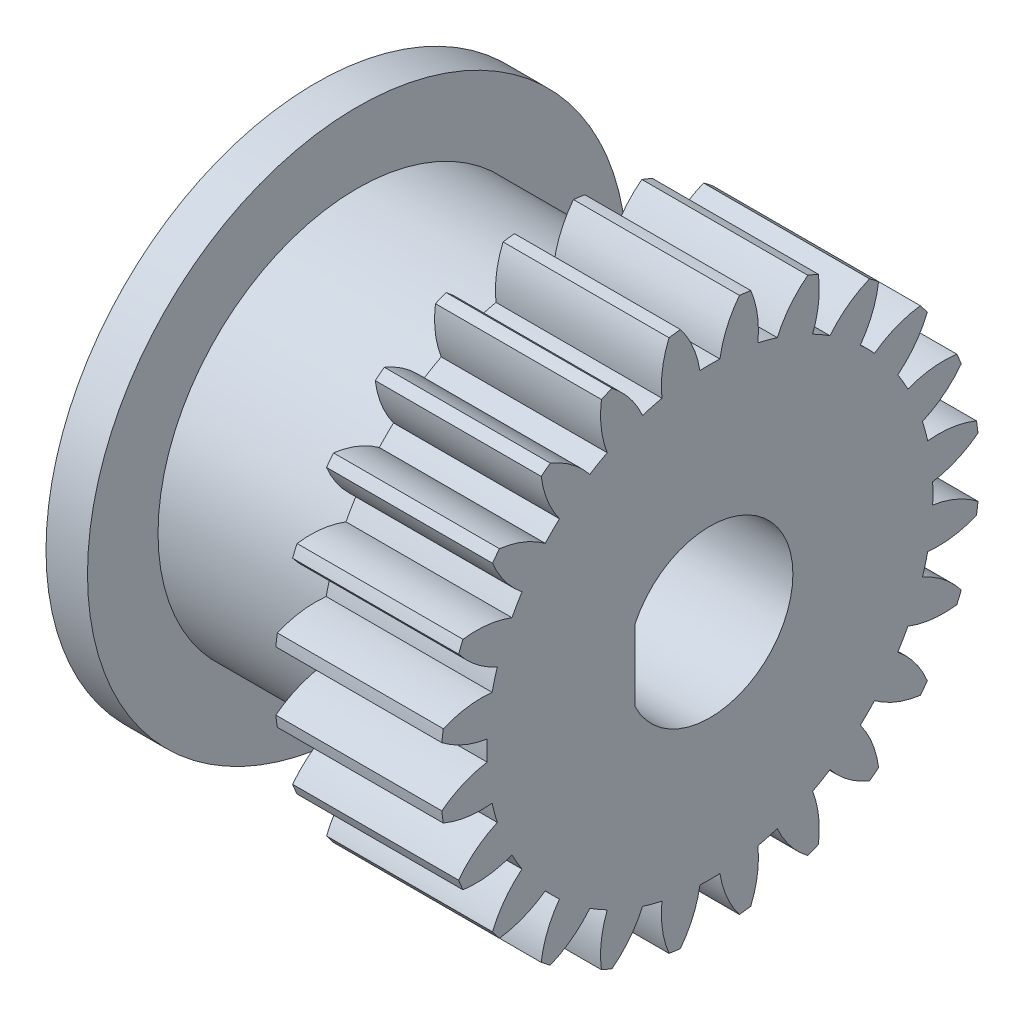
SolidWorks part; units mm, degrees
ref_plane "Plane1" through (0, 0, 0) normal (0, 0, 1) x (1, 0, 0)
ref_plane "Plane2" through (0, 0, 0) normal (0, 1, 0) x (1, 0, 0)
ref_plane "Plane3" through (0, 0, 0) normal (1, 0, 0) x (0, 0, -1)
sketch "HoldingSke" plane through (0, 0, 0) normal (0, 1, 0) x (1, 0, 0)
  line L0 (0, 0) -> (1.8271, -0.8135)
  line L1 (-15, 0) -> (100, 0) construction
  line L2 (0, 0) -> (-2.1039, 2.3779)
  line L3 (0, 0) -> (-11.863, 4.5341)
  line L4 (0, 0) -> (7.8894, 3.5126)
  line L5 (0, 0) -> (-46.8476, -17.4728)
  line L6 (0, 0) -> (-3.3159, -2.2372)
  line L7 (-2.1039, 2.3779) -> (8.6586, 51.2059)
  line L8 (-76.2, 54.61) -> (-75.7, 54.61)
  line L9 (-71.009, 38.7566) -> (-53.1078, 45.2721)
  line L10 (-76.2, 71.12) -> (104.1128, 71.12)
  line L11 (0, 0) -> (-4, 0)
  line L12 (-76.2, 101.6) -> (-76.181, 101.6)
  line L13 (24.9733, 27.94) -> (52.9518, 28.4284)
  line L14 (24.9733, 27.94) -> (24.9743, 27.94)
  line L15 (24.9733, 27.94) -> (100.4006, 29.5858)
  line L16 (-63.627, -0.5) -> (-12.827, -0.5)
  circle A0 centre (0, 0) radius 1.5
  circle A1 centre (0, 0) radius 5.374
  circle A2 centre (0, 0) radius 37.5
  circle A3 centre (0, 0) radius 1.5
  dimension "MHD" = 10.748
  dimension "Hub_dia" = 75
  dimension "Bore" = 3
  dimension "MBD" = 3
  dimension "Num_teeth" = 24
  dimension "Pitch" = 2
  dimension "Overall_len" = 50
  dimension "Show_teeth" = 24
  dimension "Thickness" = 4
  dimension "OAL" = 50.0001
  dimension "T_dim" = 0.5
  dimension "Ap" = 20
  dimension "H" = 19.05
  dimension "Pitch_radius" = 180.3128
  dimension "Width" = 4
  dimension "Backlash" = 0.019
  dimension "Addendum_fac" = 1
  dimension "Dedendum_fac" = 1.25
  dimension "Clearance_fac" = 0.25
  dimension "Dedendum_add" = 0.001
  dimension "Module" = 0.5
sketch "BasProSke" plane through (0, 0, 0) normal (0, 1, 0) x (1, 0, 0)
  line L0 (-10, 0) -> (60, 0) construction
  line L1 (0, 0) -> (0, 6.5)
  line L2 (0, 0) -> (4, 0)
  line L3 (4, 0) -> (4, 6.5)
  line L4 (4, 6.5) -> (0, 6.5)
  dimension "Thickness" = 4
  dimension "Diameter" = 13
revolve "Base-Revolve" add sketch "BasProSke" angle 360 about L0
sketch "TooCutSke" plane through (0, 0, 0) normal (1, 0, 0) x (0, 0, -1)
  line L1 (0, 0) -> (0, 107) construction
  line L2 (0, 0) -> (-0.4257, 5.9849) construction
  line L3 (0, 0) -> (-1.5635, 11.876) construction
  line L4 (-0.4257, 5.9849) -> (-0.7818, 5.938) construction
  arc A0 (0.2416, 5.3686) -> (-0.2416, 5.3686) centre (0, 0) ccw
  arc A1 (0.7297, 6.4845) -> (-0.7297, 6.4845) centre (0, 0) ccw
  circle A2 centre (0, 0) radius 6 construction
  circle A3 centre (0, 0) radius 5.6382 construction
  arc A4 (-0.2416, 5.3686) -> (-0.7297, 6.4845) centre (-2.6126, 4.9963) ccw
  arc A5 (0.7297, 6.4845) -> (0.2416, 5.3686) centre (2.6126, 4.9963) ccw
  dimension "Root_dia" = 10.748
  dimension "Overcut_dia" = 13.0508
  dimension "Pitch_dia" = 12
  dimension "Base_dia" = 11.2763
  dimension "Flank_rad" = 2.4
  dimension "Half_ang" = 7.5
  dimension "Half_CT" = 0.3592
extrude "ToothCut" cut sketch "TooCutSke" along normal through all
fillet "Breaks" [suppressed] radius 0.01
fillet "RootFillets" [suppressed] radius 0.126
pattern_circular "TeethCuts" count 24 every 15 about axis through (-10, 0, 0) along (1, 0, 0) of "ToothCut", "RootFillets", "Breaks"
sketch "HubNeaOneSke" plane through (0, 0, 0) normal (-1, 0, 0) x (0, 0, 1)
  circle A0 centre (0, 0) radius 5.374
  dimension "Diameter" = 10.748
extrude "HubNearOne" [suppressed] add sketch "HubNeaOneSke" along normal blind 46.0001
sketch "HubNeaBotSke" plane through (0, 0, 0) normal (-1, 0, 0) x (0, 0, 1)
  circle A0 centre (0, 0) radius 5.374
  dimension "Diameter" = 10.748
extrude "HubNearBoth" [suppressed] add sketch "HubNeaBotSke" along normal blind 23
ref_plane "FarPln" through (4, 0, 0) normal (1, 0, 0) x (0, 0, -1)
sketch "HubFarSke" plane through (4, 0, 0) normal (1, 0, 0) x (0, 0, -1)
  circle A0 centre (0, 0) radius 5.374
  dimension "Diameter" = 10.748
extrude "HubFar" [suppressed] add sketch "HubFarSke" along normal blind 23
sketch "BorSke" plane through (0, 0, 0) normal (1, 0, 0) x (0, 0, -1)
  circle A0 centre (0, 0) radius 1.5
  dimension "Diameter" = 3
extrude "Bore" cut sketch "BorSke" along normal mid plane 100.0001
sketch "KeySke" plane through (0, 0, 0) normal (1, 0, 0) x (0, 0, -1)
  line L0 (-0.6, 0) -> (-0.6, 2)
  line L1 (-0.6, 2) -> (0.6, 2)
  line L2 (0.6, 2) -> (0.6, 0)
  line L3 (0, 0) -> (0, 34) construction
  line L4 (-0.6, 0) -> (0.6, 0)
  dimension "Offset" = 2
  dimension "Width" = 1.2
extrude "Keyway" [suppressed] cut sketch "KeySke" along normal mid plane 100.0001
pattern_circular "Keyway2" [suppressed] count 2 every 90 about axis through (-10, 0, 0) along (1, 0, 0)
sketch "草图1" plane through (0, 0, 0) normal (-1, 0, 0) x (0, 0, 1)
  circle A0 centre (0, 0) radius 4.8
  circle A1 centre (0, 0) radius 1.5
extrude "凸台-拉伸1" add sketch "草图1" along normal blind 4.5
sketch "草图2" plane through (-4.5, 0, 0) normal (-1, 0, 0) x (0, 0, 1)
  circle A0 centre (0, 0) radius 1.5
  circle A1 centre (0, 0) radius 6.5
extrude "凸台-拉伸2" add sketch "草图2" along normal blind 1
sketch "草图3" plane through (-5.5, 0, 0) normal (-1, 0, 0) x (0, 0, 1)
  line L0 (1.8, -0.8718) -> (1.8, 0.8718)
  arc A0 (1.8, 0.8718) -> (1.8, -0.8718) centre (0, 0) ccw
  point P5 (0, 0)
extrude "切除-拉伸1" cut sketch "草图3" against normal up to next
equation "' \"Module@HoldingSke\" = 6.35"
equation "' \"Num_teeth@HoldingSke\" = 12"
equation "' \"Ap@HoldingSke\" =  20"
equation "' \"Ap@HoldingSke\" = 20"
equation "' \"Width@HoldingSke\" = 0.5 * 25.4"
equation "' \"Hub_dia@HoldingSke\"= 1 * 25.4"
equation "' \"Hub_dia@HoldingSke\" = 1 * 25.4"
equation "' \"Overall_len@HoldingSke\" = 1.0 * 25.4"
equation "' \"Bore@HoldingSke\" = 0.75 * 25.4"
equation "' \"T_dim@HoldingSke\" = 0.1 * 25.4"
equation "' \"Width@KeySke\" = 0.25 * 25.4"
equation "' \"Show_teeth@HoldingSke\" = 13"
equation "' \"Backlash@HoldingSke\" = 0.009 * 25.4"
equation "' \"Addendum_fac@HoldingSke\" = 1.0"
equation "' \"Dedendum_fac@HoldingSke\" = 1.25"
equation "' \"Dedendum_add@HoldingSke\" = 0.00005 * 25.4"
equation "' \"Clearance_fac@HoldingSke\" = 0.25"
equation "\"Pitch@HoldingSke\" = 1 / \"Module@HoldingSke\""
equation "\"Overcut_dia@TooCutSke\" = (\"Num_teeth@HoldingSke\" + 2 * \"Addendum_fac@HoldingSke\") / \"Pitch@HoldingSke\" + 0.002 * 25.4"
equation "\"Pitch_dia@TooCutSke\" = \"Num_teeth@HoldingSke\" / \"Pitch@HoldingSke\""
equation "\"Base_dia@TooCutSke\" = \"Num_teeth@HoldingSke\" / \"Pitch@HoldingSke\" * cos((\"Ap@HoldingSke\"  * 3.14159265 / 180))"
equation "\"Root_dia@TooCutSke\" = (\"Num_teeth@HoldingSke\" + 2) / \"Pitch@HoldingSke\" - 2 * (\"Addendum_fac@HoldingSke\" + \"Dedendum_fac@HoldingSke\") / \"Pitch@HoldingSke\" - \"Dedendum_add@HoldingSke\" * 2"
equation "\"Half_ang@TooCutSke\" = 180 / \"Num_teeth@HoldingSke\""
equation "\"Half_CT@TooCutSke\" = \"Num_teeth@HoldingSke\" / \"Pitch@HoldingSke\" * sin((3.14159265 / 2 / \"Num_teeth@HoldingSke\")) / 2 - 7 * \"Backlash@HoldingSke\" / 4"
equation "\"Flank_rad@TooCutSke\" = \"Num_teeth@HoldingSke\" / \"Pitch@HoldingSke\" / 5"
equation "\"Radius@RootFillets\" = \"Clearance_fac@HoldingSke\" / \"Pitch@HoldingSke\" + \"Dedendum_add@HoldingSke\""
equation "\"Break_rad@Breaks\" = 0.02 / \"Pitch@HoldingSke\""
equation "\"Thickness@HoldingSke\" = \"Width@HoldingSke\""
equation "\"OAL@HoldingSke\" = \"Thickness@HoldingSke\""
equation "\"MHD@HoldingSke\" = (\"Num_teeth@HoldingSke\" + 2) / \"Pitch@HoldingSke\" - 2 * (\"Addendum_fac@HoldingSke\" + \"Dedendum_fac@HoldingSke\")  / \"Pitch@HoldingSke\" - \"Dedendum_add@HoldingSke\" * 2"
equation "\"MBD@HoldingSke\" = (\"Num_teeth@HoldingSke\" + 2) / \"Pitch@HoldingSke\" - 2 * (\"Addendum_fac@HoldingSke\" + \"Dedendum_fac@HoldingSke\")  / \"Pitch@HoldingSke\" - \"Dedendum_add@HoldingSke\" * 2 - 0.002 * 25.4"
equation "\"MHD@HoldingSke\" = ((sgn( \"MHD@HoldingSke\" - \"Hub_dia@HoldingSke\" )-1)*( \"MHD@HoldingSke\" - \"Hub_dia@HoldingSke\" ))/-2+ \"Hub_dia@HoldingSke\""
equation "\"MBD@HoldingSke\" = ((sgn( \"MBD@HoldingSke\" - \"Bore@HoldingSke\" )-1)*( \"MBD@HoldingSke\" - \"Bore@HoldingSke\" ))/-2+ \"Bore@HoldingSke\""
equation "\"OAL@HoldingSke\" = ((sgn( \"OAL@HoldingSke\" - \"Overall_len@HoldingSke\" )+1)*( \"OAL@HoldingSke\" - \"Overall_len@HoldingSke\" ))/2 + \"Overall_len@HoldingSke\" + 0.000002 * 25.4"
equation "\"Num_teeth@TeethCuts\" = int( \"Show_teeth@HoldingSke\" ) + 1"
equation "\"Num_teeth@TeethCuts\" = ((sgn( \"Num_teeth@TeethCuts\" - \"Num_teeth@HoldingSke\" )-1)*( \"Num_teeth@TeethCuts\" - \"Num_teeth@HoldingSke\" ))/-2+ \"Num_teeth@HoldingSke\""
equation "\"Num_teeth@TeethCuts\" = ((sgn( \"Num_teeth@TeethCuts\" - 2.0)+1)*( \"Num_teeth@TeethCuts\" - 2.0))/2 +2.0"
equation "\"Angle@TeethCuts\" = 360.0 / \"Num_teeth@HoldingSke\""
equation "\"Diameter@BasProSke\" = (\"Num_teeth@HoldingSke\" + 2 * \"Addendum_fac@HoldingSke\") / \"Pitch@HoldingSke\""
equation "\"Thickness@BasProSke\"  = \"Thickness@HoldingSke\""
equation "' \"Fillet_rad@BasProSke\" =  \"Thickness@HoldingSke\" * 0.05"
equation "' \"Fillet_rad@BasProSke\" = \"Thickness@HoldingSke\" * 0.05"
equation "\"MHD@HoldingSke\" = ((sgn( \"MHD@HoldingSke\" - \"Root_dia@TooCutSke\" )-1)*( \"MHD@HoldingSke\" - \"Root_dia@TooCutSke\" ))/-2+ \"Root_dia@TooCutSke\""
equation "\"Diameter@HubNeaOneSke\" = \"MHD@HoldingSke\""
equation "\"Length@HubNearOne\" = \"OAL@HoldingSke\" - \"Thickness@BasProSke\""
equation "\"Diameter@HubNeaBotSke\" = \"MHD@HoldingSke\""
equation "\"Length@HubNearBoth\" = ( \"OAL@HoldingSke\" - \"Thickness@BasProSke\" ) / 2.0"
equation "\"Thickness@FarPln\" = \"Thickness@BasProSke\""
equation "\"Diameter@HubFarSke\" = \"MHD@HoldingSke\""
equation "\"Length@HubFar\" = ( \"OAL@HoldingSke\" - \"Thickness@BasProSke\" ) / 2.0"
equation "\"Diameter@BorSke\" = \"MBD@HoldingSke\""
equation "\"D1@Bore\" = \"OAL@HoldingSke\" * 2.0"
equation "\"D1@Keyway\" = \"OAL@HoldingSke\" * 2.0"
equation "\"Offset@KeySke\" = \"T_dim@HoldingSke\" + \"MBD@HoldingSke\" / 2.0"
